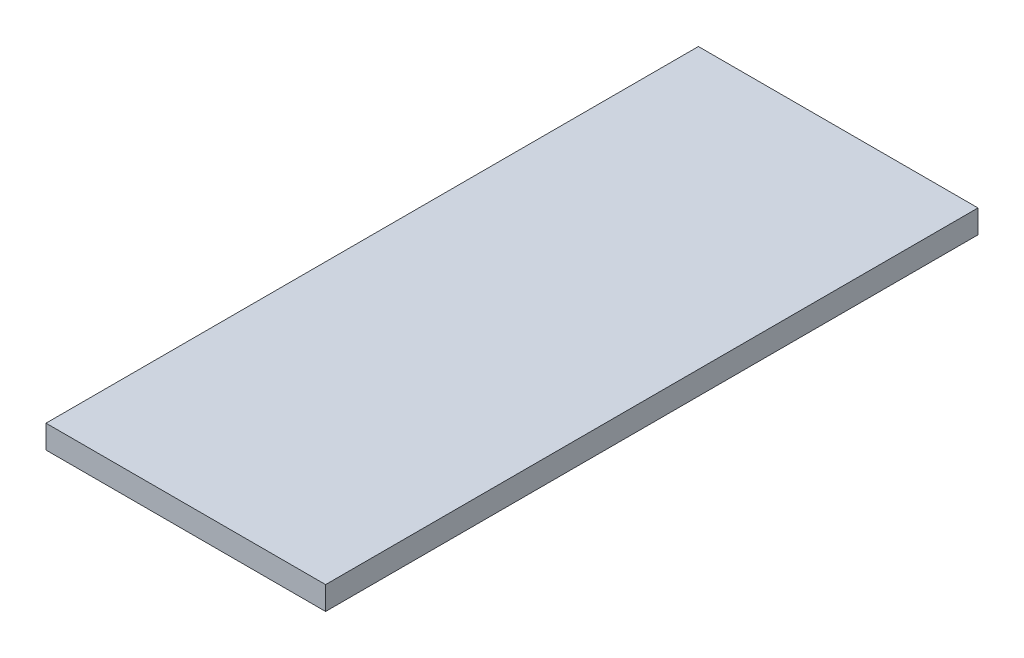
SolidWorks part; units mm, degrees
ref_plane "Front Plane" through (0, 0, 0) normal (0, 0, 1) x (1, 0, 0)
ref_plane "Top Plane" through (0, 0, 0) normal (0, 1, 0) x (1, 0, 0)
ref_plane "Right Plane" through (0, 0, 0) normal (1, 0, 0) x (0, 0, -1)
sketch "Sketch1" plane through (0, 0, 0) normal (0, 1, 0) x (1, 0, 0)
  line L1 (0, 0) -> (300, 0)
  line L2 (0, 0) -> (0, 700)
  line L3 (0, 700) -> (300, 700)
  line L4 (300, 0) -> (300, 700)
  dimension "D1" = 300
  dimension "D2" = 700
extrude "Boss-Extrude1" add sketch "Sketch1" along normal blind 25
